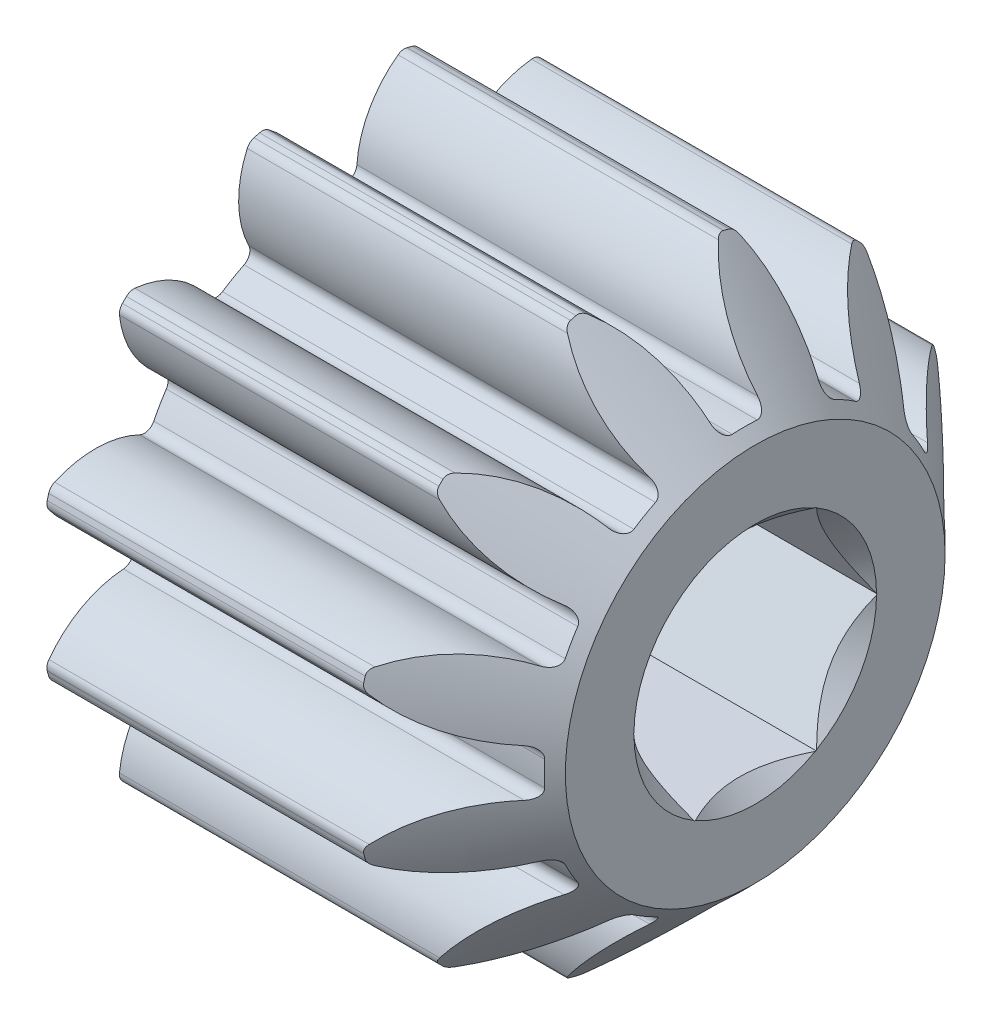
SolidWorks part; units mm, degrees
ref_plane "Plane1" through (0, 0, 0) normal (0, 0, 1) x (1, 0, 0)
ref_plane "Plane2" through (0, 0, 0) normal (0, 1, 0) x (1, 0, 0)
ref_plane "Plane3" through (0, 0, 0) normal (1, 0, 0) x (0, 0, -1)
sketch "HoldingSke" plane through (0, 0, 0) normal (0, 1, 0) x (1, 0, 0)
  line L0 (0, 0) -> (0.4891, -0.104)
  line L1 (-15, 0) -> (100, 0) construction
  line L2 (0, 0) -> (-2.1039, 2.3779)
  line L3 (0, 0) -> (-11.863, 4.5341)
  line L4 (0, 0) -> (8.4473, 1.7955)
  line L5 (0, 0) -> (-46.8476, -17.4728)
  line L6 (0, 0) -> (-13.2634, -8.9489)
  line L7 (-2.1039, 2.3779) -> (8.6586, 51.2059)
  line L8 (-76.2, 54.61) -> (-75.2, 54.61)
  line L9 (-71.009, 38.7566) -> (-53.1078, 45.2721)
  line L10 (-76.2, 71.12) -> (104.1128, 71.12)
  line L11 (0, 0) -> (-16, 0)
  line L12 (-76.2, 101.6) -> (-76.133, 101.6)
  line L13 (24.9733, 27.94) -> (52.9518, 28.4284)
  line L14 (24.9733, 27.94) -> (24.9743, 27.94)
  line L15 (24.9733, 27.94) -> (100.4006, 29.5858)
  line L16 (-63.627, -2) -> (-12.827, -2)
  circle A0 centre (0, 0) radius 3
  circle A1 centre (0, 0) radius 9.499
  circle A2 centre (0, 0) radius 37.5
  circle A3 centre (0, 0) radius 3
  dimension "MHD" = 18.998
  dimension "Hub_dia" = 75
  dimension "Bore" = 6
  dimension "MBD" = 6
  dimension "Num_teeth" = 12
  dimension "Pitch" = 0.5
  dimension "Overall_len" = 50
  dimension "Show_teeth" = 12
  dimension "Thickness" = 16
  dimension "OAL" = 50.0001
  dimension "T_dim" = 1
  dimension "Ap" = 20
  dimension "H" = 19.05
  dimension "Pitch_radius" = 180.3128
  dimension "Width" = 16
  dimension "Backlash" = 0.067
  dimension "Addendum_fac" = 1
  dimension "Dedendum_fac" = 1.25
  dimension "Clearance_fac" = 0.25
  dimension "Dedendum_add" = 0.001
  dimension "Module" = 2
sketch "BasProSke" plane through (0, 0, 0) normal (0, 1, 0) x (1, 0, 0)
  line L0 (-10, 0) -> (60, 0) construction
  line L1 (0, 0) -> (0, 14)
  line L2 (0, 0) -> (20, 0)
  line L3 (20, 0) -> (20, 14)
  line L4 (20, 14) -> (0, 14)
  dimension "Thickness" = 20
  dimension "Diameter" = 28
revolve "Base-Revolve" add sketch "BasProSke" angle 360 about L0
sketch "TooCutSke" plane through (0, 0, 0) normal (1, 0, 0) x (0, 0, -1)
  line L1 (0, 0) -> (0, 107) construction
  line L2 (0, 0) -> (-1.6834, 11.8813) construction
  line L3 (0, 0) -> (-6.1662, 23.0126) construction
  line L4 (-1.6834, 11.8813) -> (-3.0831, 11.5063) construction
  arc A0 (1.1119, 9.4337) -> (-1.1119, 9.4337) centre (0, 0) ccw
  arc A1 (3.2981, 13.6321) -> (-3.2981, 13.6321) centre (0, 0) ccw
  circle A2 centre (0, 0) radius 12 construction
  circle A3 centre (0, 0) radius 11.2763 construction
  arc A4 (-1.1119, 9.4337) -> (-3.2981, 13.6321) centre (-5.9089, 9.6042) ccw
  arc A5 (3.2981, 13.6321) -> (1.1119, 9.4337) centre (5.9089, 9.6042) ccw
  dimension "Root_dia" = 18.998
  dimension "Overcut_dia" = 28.0508
  dimension "Pitch_dia" = 24
  dimension "Base_dia" = 22.5526
  dimension "Flank_rad" = 4.8
  dimension "Half_ang" = 15
  dimension "Half_CT" = 1.4491
extrude "ToothCut" cut sketch "TooCutSke" along normal through all
fillet "Breaks" [suppressed] radius 0.04
fillet "RootFillets" [suppressed] radius 0.501
pattern_circular "TeethCuts" count 12 every 30 about axis through (-10, 0, 0) along (1, 0, 0) of "ToothCut", "RootFillets", "Breaks"
sketch "HubNeaOneSke" plane through (0, 0, 0) normal (-1, 0, 0) x (0, 0, 1)
  circle A0 centre (0, 0) radius 9.499
  dimension "Diameter" = 18.998
extrude "HubNearOne" [suppressed] add sketch "HubNeaOneSke" along normal blind 30.0001
sketch "HubNeaBotSke" plane through (0, 0, 0) normal (-1, 0, 0) x (0, 0, 1)
  circle A0 centre (0, 0) radius 9.499
  dimension "Diameter" = 18.998
extrude "HubNearBoth" [suppressed] add sketch "HubNeaBotSke" along normal blind 15
ref_plane "FarPln" through (20, 0, 0) normal (1, 0, 0) x (0, 0, -1)
sketch "HubFarSke" plane through (20, 0, 0) normal (1, 0, 0) x (0, 0, -1)
  circle A0 centre (0, 0) radius 9.499
  dimension "Diameter" = 18.998
extrude "HubFar" [suppressed] add sketch "HubFarSke" along normal blind 15
sketch "BorSke" plane through (0, 0, 0) normal (1, 0, 0) x (0, 0, -1)
  circle A0 centre (0, 0) radius 3
  dimension "Diameter" = 6
extrude "Bore" cut sketch "BorSke" along normal mid plane 100.0001
sketch "KeySke" plane through (0, 0, 0) normal (1, 0, 0) x (0, 0, -1)
  line L0 (-1, 0) -> (-1, 4)
  line L1 (-1, 4) -> (1, 4)
  line L2 (1, 4) -> (1, 0)
  line L3 (0, 0) -> (0, 34) construction
  line L4 (-1, 0) -> (1, 0)
  dimension "Offset" = 4
  dimension "Width" = 2
extrude "Keyway" [suppressed] cut sketch "KeySke" along normal mid plane 100.0001
pattern_circular "Keyway2" [suppressed] count 2 every 90 about axis through (-10, 0, 0) along (1, 0, 0)
fillet "Скругление1" radius 0.5 24 edges at (10, 7.6139, -5.6798) (10, 8.7258, -3.7539) (10, 3.7539, -8.7258) (10, 5.6798, -7.6139) (10, -1.1119, -9.4337) (10, 1.1119, -9.4337) (10, -5.6798, -7.6139) (10, -3.7539, -8.7258) (10, -8.7258, -3.7539) (10, -7.6139, -5.6798) (10, -9.4337, 1.1119) (10, -9.4337, -1.1119) (10, -7.6139, 5.6798) (10, -8.7258, 3.7539) (10, -3.7539, 8.7258) (10, 1.1119, 9.4337) (10, -1.1119, 9.4337) (10, 5.6798, 7.6139) (10, 3.7539, 8.7258) (10, 8.7258, 3.7539) (10, 7.6139, 5.6798) (10, -5.6798, 7.6139) (10, 9.4337, -1.1119) (10, 9.4337, 1.1119)
sketch "Эскиз1" plane through (20, 0, 0) normal (1, 0, 0) x (0, 0, -1)
  line L1 (2.8868, 5) -> (-2.8868, 5)
  line L2 (-2.8868, 5) -> (-5.7735, 0)
  line L3 (-5.7735, 0) -> (-2.8868, -5)
  line L4 (-2.8868, -5) -> (2.8868, -5)
  line L5 (2.8868, -5) -> (5.7735, 0)
  line L6 (5.7735, 0) -> (2.8868, 5)
  circle A0 centre (0, 0) radius 5 construction
  dimension "D1" = 10
extrude "Вырез-Вытянуть1" cut sketch "Эскиз1" against normal through all
sketch "Эскиз2" plane through (20, 0, 0) normal (1, 0, 0) x (0, 0, -1)
  circle A0 centre (0, 0) radius 9
  dimension "D1" = 18
extrude "Вырез-Вытянуть2" cut sketch "Эскиз2" against normal blind 10 draft 45 flip side to cut
fillet "Скругление2" radius 0.5 24 edges at (7.5, 3.2689, 13.613) (7.5, -3.2689, 13.613) (7.5, -3.9755, 13.4237) (7.5, -9.6375, 10.1547) (7.5, -10.1547, 9.6375) (7.5, -13.4237, 3.9755) (7.5, -13.613, 3.2689) (7.5, -13.613, -3.2689) (7.5, -13.4237, -3.9755) (7.5, -10.1547, -9.6375) (7.5, -9.6375, -10.1547) (7.5, -3.9755, -13.4237) (7.5, -3.2689, -13.613) (7.5, 3.2689, -13.613) (7.5, 3.9755, -13.4237) (7.5, 9.6375, -10.1547) (7.5, 10.1547, -9.6375) (7.5, 13.4237, -3.9755) (7.5, 13.613, -3.2689) (7.5, 13.613, 3.2689) (7.5, 13.4237, 3.9755) (7.5, 10.1547, 9.6375) (7.5, 9.6375, 10.1547) (7.5, 3.9755, 13.4237)
sketch "Эскиз3" plane through (20, 0, 0) normal (1, 0, 0) x (0, 0, -1)
  circle A0 centre (0, 0) radius 5.75
  dimension "D1" = 11.5
extrude "Вырез-Вытянуть3" cut sketch "Эскиз3" against normal blind 10 draft 45
equation "' \"Module@HoldingSke\" = 6.35"
equation "' \"Num_teeth@HoldingSke\" = 12"
equation "' \"Ap@HoldingSke\" =  20"
equation "' \"Ap@HoldingSke\" = 20"
equation "' \"Width@HoldingSke\" = 0.5 * 25.4"
equation "' \"Hub_dia@HoldingSke\"= 1 * 25.4"
equation "' \"Hub_dia@HoldingSke\" = 1 * 25.4"
equation "' \"Overall_len@HoldingSke\" = 1.0 * 25.4"
equation "' \"Bore@HoldingSke\" = 0.75 * 25.4"
equation "' \"T_dim@HoldingSke\" = 0.1 * 25.4"
equation "' \"Width@KeySke\" = 0.25 * 25.4"
equation "' \"Show_teeth@HoldingSke\" = 13"
equation "' \"Backlash@HoldingSke\" = 0.009 * 25.4"
equation "' \"Addendum_fac@HoldingSke\" = 1.0"
equation "' \"Dedendum_fac@HoldingSke\" = 1.25"
equation "' \"Dedendum_add@HoldingSke\" = 0.00005 * 25.4"
equation "' \"Clearance_fac@HoldingSke\" = 0.25"
equation "\"Pitch@HoldingSke\" = 1 / \"Module@HoldingSke\""
equation "\"Overcut_dia@TooCutSke\" = (\"Num_teeth@HoldingSke\" + 2 * \"Addendum_fac@HoldingSke\") / \"Pitch@HoldingSke\" + 0.002 * 25.4"
equation "\"Pitch_dia@TooCutSke\" = \"Num_teeth@HoldingSke\" / \"Pitch@HoldingSke\""
equation "\"Base_dia@TooCutSke\" = \"Num_teeth@HoldingSke\" / \"Pitch@HoldingSke\" * cos((\"Ap@HoldingSke\"  * 3.14159265 / 180))"
equation "\"Root_dia@TooCutSke\" = (\"Num_teeth@HoldingSke\" + 2) / \"Pitch@HoldingSke\" - 2 * (\"Addendum_fac@HoldingSke\" + \"Dedendum_fac@HoldingSke\") / \"Pitch@HoldingSke\" - \"Dedendum_add@HoldingSke\" * 2"
equation "\"Half_ang@TooCutSke\" = 180 / \"Num_teeth@HoldingSke\""
equation "\"Half_CT@TooCutSke\" = \"Num_teeth@HoldingSke\" / \"Pitch@HoldingSke\" * sin((3.14159265 / 2 / \"Num_teeth@HoldingSke\")) / 2 - 7 * \"Backlash@HoldingSke\" / 4"
equation "\"Flank_rad@TooCutSke\" = \"Num_teeth@HoldingSke\" / \"Pitch@HoldingSke\" / 5"
equation "\"Radius@RootFillets\" = \"Clearance_fac@HoldingSke\" / \"Pitch@HoldingSke\" + \"Dedendum_add@HoldingSke\""
equation "\"Break_rad@Breaks\" = 0.02 / \"Pitch@HoldingSke\""
equation "\"Thickness@HoldingSke\" = \"Width@HoldingSke\""
equation "\"OAL@HoldingSke\" = \"Thickness@HoldingSke\""
equation "\"MHD@HoldingSke\" = (\"Num_teeth@HoldingSke\" + 2) / \"Pitch@HoldingSke\" - 2 * (\"Addendum_fac@HoldingSke\" + \"Dedendum_fac@HoldingSke\")  / \"Pitch@HoldingSke\" - \"Dedendum_add@HoldingSke\" * 2"
equation "\"MBD@HoldingSke\" = (\"Num_teeth@HoldingSke\" + 2) / \"Pitch@HoldingSke\" - 2 * (\"Addendum_fac@HoldingSke\" + \"Dedendum_fac@HoldingSke\")  / \"Pitch@HoldingSke\" - \"Dedendum_add@HoldingSke\" * 2 - 0.002 * 25.4"
equation "\"MHD@HoldingSke\" = ((sgn( \"MHD@HoldingSke\" - \"Hub_dia@HoldingSke\" )-1)*( \"MHD@HoldingSke\" - \"Hub_dia@HoldingSke\" ))/-2+ \"Hub_dia@HoldingSke\""
equation "\"MBD@HoldingSke\" = ((sgn( \"MBD@HoldingSke\" - \"Bore@HoldingSke\" )-1)*( \"MBD@HoldingSke\" - \"Bore@HoldingSke\" ))/-2+ \"Bore@HoldingSke\""
equation "\"OAL@HoldingSke\" = ((sgn( \"OAL@HoldingSke\" - \"Overall_len@HoldingSke\" )+1)*( \"OAL@HoldingSke\" - \"Overall_len@HoldingSke\" ))/2 + \"Overall_len@HoldingSke\" + 0.000002 * 25.4"
equation "\"Num_teeth@TeethCuts\" = int( \"Show_teeth@HoldingSke\" ) + 1"
equation "\"Num_teeth@TeethCuts\" = ((sgn( \"Num_teeth@TeethCuts\" - \"Num_teeth@HoldingSke\" )-1)*( \"Num_teeth@TeethCuts\" - \"Num_teeth@HoldingSke\" ))/-2+ \"Num_teeth@HoldingSke\""
equation "\"Num_teeth@TeethCuts\" = ((sgn( \"Num_teeth@TeethCuts\" - 2.0)+1)*( \"Num_teeth@TeethCuts\" - 2.0))/2 +2.0"
equation "\"Angle@TeethCuts\" = 360.0 / \"Num_teeth@HoldingSke\""
equation "\"Diameter@BasProSke\" = (\"Num_teeth@HoldingSke\" + 2 * \"Addendum_fac@HoldingSke\") / \"Pitch@HoldingSke\""
equation "' \"Fillet_rad@BasProSke\" =  \"Thickness@HoldingSke\" * 0.05"
equation "' \"Fillet_rad@BasProSke\" = \"Thickness@HoldingSke\" * 0.05"
equation "\"MHD@HoldingSke\" = ((sgn( \"MHD@HoldingSke\" - \"Root_dia@TooCutSke\" )-1)*( \"MHD@HoldingSke\" - \"Root_dia@TooCutSke\" ))/-2+ \"Root_dia@TooCutSke\""
equation "\"Diameter@HubNeaOneSke\" = \"MHD@HoldingSke\""
equation "\"Length@HubNearOne\" = \"OAL@HoldingSke\" - \"Thickness@BasProSke\""
equation "\"Diameter@HubNeaBotSke\" = \"MHD@HoldingSke\""
equation "\"Length@HubNearBoth\" = ( \"OAL@HoldingSke\" - \"Thickness@BasProSke\" ) / 2.0"
equation "\"Thickness@FarPln\" = \"Thickness@BasProSke\""
equation "\"Diameter@HubFarSke\" = \"MHD@HoldingSke\""
equation "\"Length@HubFar\" = ( \"OAL@HoldingSke\" - \"Thickness@BasProSke\" ) / 2.0"
equation "\"Diameter@BorSke\" = \"MBD@HoldingSke\""
equation "\"D1@Bore\" = \"OAL@HoldingSke\" * 2.0"
equation "\"D1@Keyway\" = \"OAL@HoldingSke\" * 2.0"
equation "\"Offset@KeySke\" = \"T_dim@HoldingSke\" + \"MBD@HoldingSke\" / 2.0"
